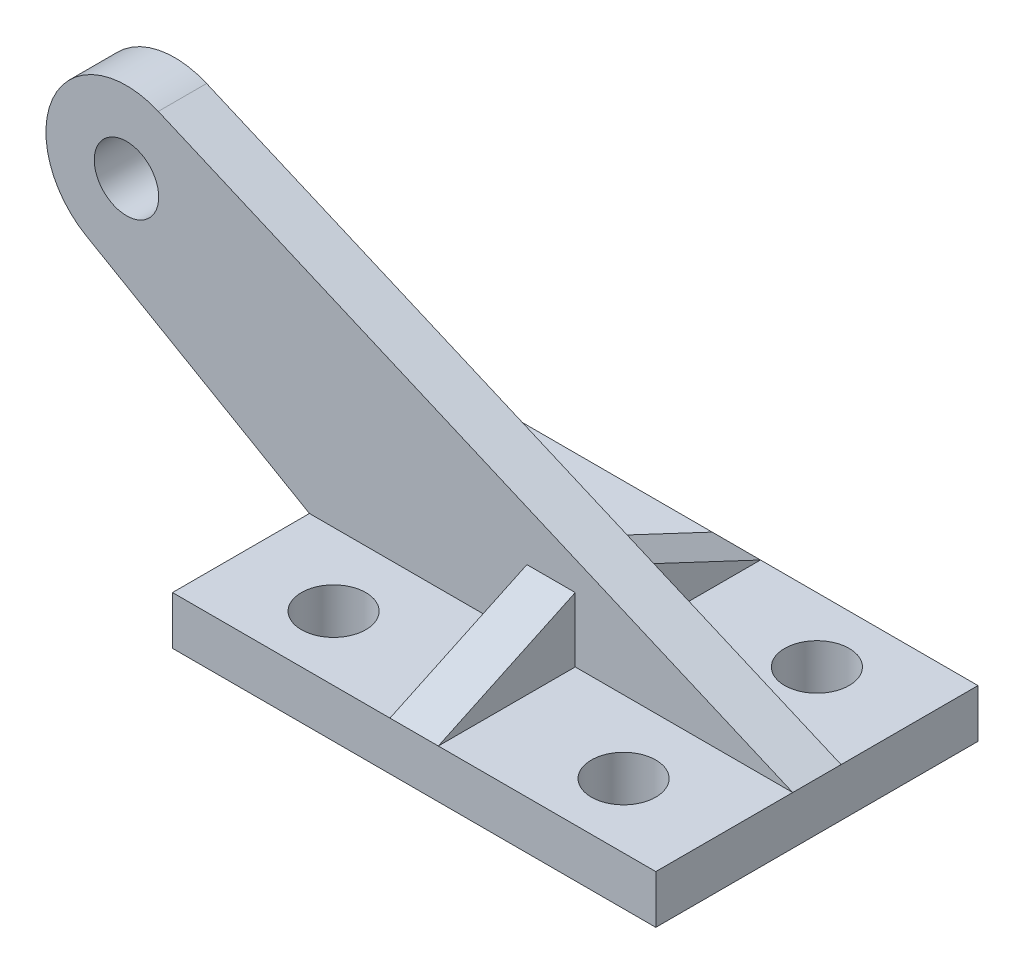
SolidWorks part; units mm, degrees
ref_plane "Front Plane" through (0, 0, 0) normal (0, 0, 1) x (1, 0, 0)
ref_plane "Top Plane" through (0, 0, 0) normal (0, 1, 0) x (1, 0, 0)
ref_plane "Right Plane" through (0, 0, 0) normal (1, 0, 0) x (0, 0, -1)
sketch "Sketch1" plane through (0, 0, 0) normal (0, 1, 0) x (1, 0, 0)
  line L1 (-75, -50) -> (75, -50)
  line L2 (-75, -50) -> (-75, 50)
  line L3 (-75, 50) -> (75, 50)
  line L4 (75, -50) -> (75, 50)
  line L5 (-75, -50) -> (75, 50) construction
  line L6 (-75, 50) -> (75, -50) construction
  circle A0 centre (-45, 30) radius 10
  circle A1 centre (45, 30) radius 10
  circle A2 centre (45, -30) radius 10
  circle A3 centre (-45, -30) radius 10
  point P0 (0, 0)
  point P14 (0, 0)
  point P15 (0, 0)
  point P16 (0, 0)
  dimension "D3" = 20
  dimension "D1" = 150
  dimension "D2" = 100
  dimension "D4" = 20
extrude "Boss-Extrude1" add sketch "Sketch1" along normal blind 15
sketch "Sketch2" plane through (0, 0, 0) normal (0, 0, 1) x (1, 0, 0)
  line L1 (-75, 15) -> (75, 15) construction
  line L2 (75, 15) -> (-75, 15)
  line L3 (-75, 15) -> (-144.282, 55)
  line L4 (-144.282, 55) -> (-119.1949, 98.4522) construction
  line L5 (-121.9115, 99.6196) -> (75, 15)
  circle A0 centre (-131.782, 76.6506) radius 10
  arc A1 (-121.9115, 99.6196) -> (-144.282, 55) centre (-131.782, 76.6506) ccw
  dimension "D4" = 50
  dimension "D3" = 20
  dimension "D1" = 150
  dimension "D2" = 80
extrude "Boss-Extrude2" add sketch "Sketch2" along normal mid plane 15
sketch "Sketch3" plane through (0, 0, 0) normal (1, 0, 0) x (0, 0, -1)
  line L0 (-7.5, 35) -> (-7.5, 15)
  line L1 (-7.5, 55) -> (-7.5, 15) construction
  line L2 (-7.5, 15) -> (-50, 15)
  line L3 (-7.5, 15) -> (-50, 15) construction
  line L4 (-50, 15) -> (-7.5, 35)
  line L5 (0, 0) -> (0, 101.6506) construction
  line L6 (7.5, 101.6506) -> (-7.5, 101.6506) construction
  line L7 (50, 15) -> (7.5, 35)
  line L8 (7.5, 15) -> (50, 15)
  line L9 (7.5, 35) -> (7.5, 15)
  dimension "D1" = 20
extrude "Boss-Extrude3" add sketch "Sketch3" along normal mid plane 15
